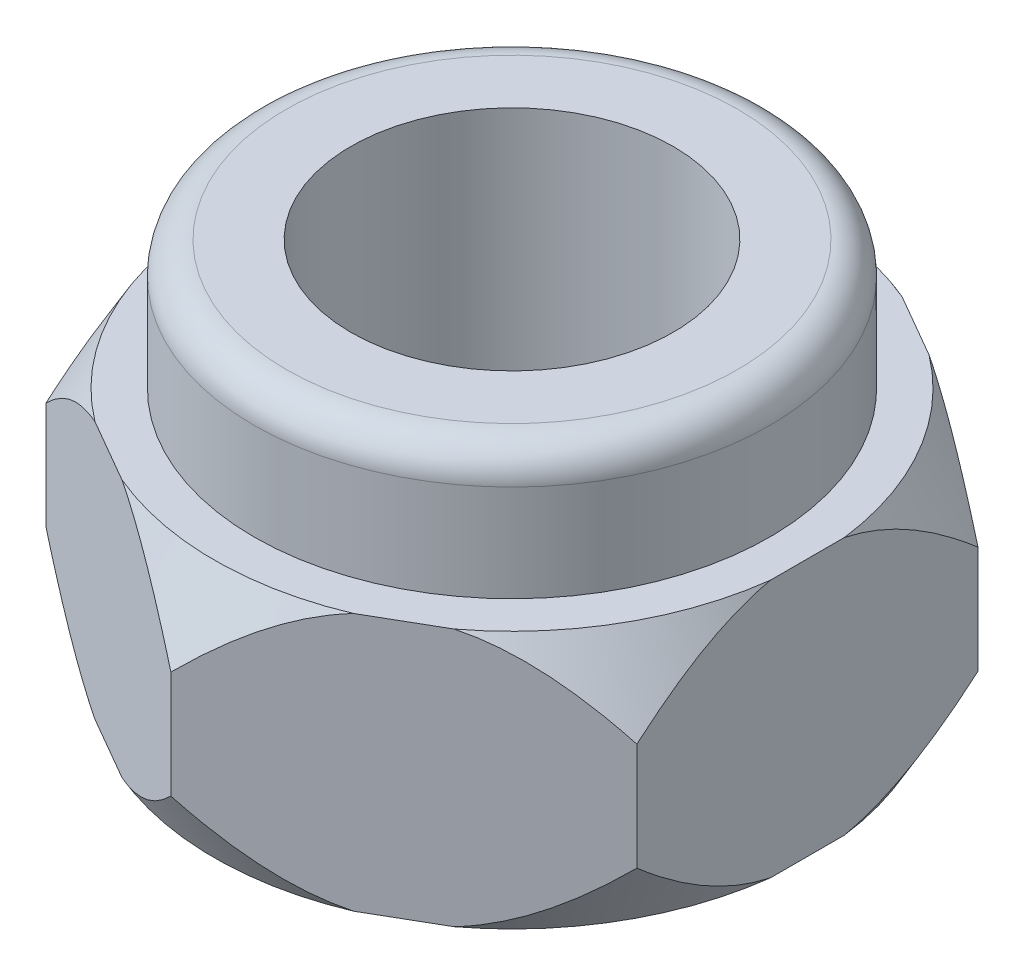
SolidWorks part; units mm, degrees
ref_plane "前视基准面" through (0, 0, 0) normal (0, 0, 1) x (1, 0, 0)
ref_plane "上视基准面" through (0, 0, 0) normal (0, 1, 0) x (1, 0, 0)
ref_plane "右视基准面" through (0, 0, 0) normal (1, 0, 0) x (0, 0, -1)
sketch "草图1" plane through (0, 0, 0) normal (0, 1, 0) x (1, 0, 0)
  line L1 (0, 3.1754) -> (-2.75, 1.5877)
  line L2 (-2.75, 1.5877) -> (-2.75, -1.5877)
  line L3 (-2.75, -1.5877) -> (0, -3.1754)
  line L4 (0, -3.1754) -> (2.75, -1.5877)
  line L5 (2.75, -1.5877) -> (2.75, 1.5877)
  line L6 (2.75, 1.5877) -> (0, 3.1754)
  circle A0 centre (0, 0) radius 2.75 construction
  circle A1 centre (0, 0) radius 1.5
  dimension "D1" = 3
  dimension "D2" = 5.5
extrude "凸台-拉伸1" add sketch "草图1" along normal blind 2.4
cosmetic thread "装饰螺纹线1" parameters "D2"=9
sketch "草图3" plane through (0, 0, 0) normal (1, 0, 0) x (0, 0, -1)
  line L0 (0, 2.4) -> (0, 7.2) construction
  line L1 (-1.5877, 2.4) -> (1.5877, 2.4) construction
  line L2 (0, 7.2) -> (3.4641, 1.2) construction
  line L3 (0.3843, 7.2) -> (4.0835, 7.2)
  line L4 (4.0835, 7.2) -> (4.0835, -4.8)
  line L5 (-1.5877, 1.2) -> (6.6733, 1.2) construction
  line L6 (-1.5877, 2.4) -> (-1.5877, 0) construction
  line L7 (0.3843, 6.5344) -> (0.3843, 7.2)
  line L8 (0.2977, -4.8) -> (4.0835, -4.8)
  line L9 (0, -4.8) -> (3.4641, 1.2) construction
  line L10 (0.2977, -4.2844) -> (0.2977, -4.8)
  line L11 (0.3843, 6.5344) -> (3.4641, 1.2)
  line L12 (3.4641, 1.2) -> (0.2977, -4.2844)
  dimension "D1" = 4.8
  dimension "D2" = 30
revolve "切除-旋转7" cut sketch "草图3" angle 360 about axis through (0, 2.4, 0) along (0, -1, 0)
sketch "草图4" plane through (0, 2.4, 0) normal (0, 1, 0) x (1, 0, 0)
  circle A0 centre (0, 0) radius 1.5
  circle A1 centre (0, 0) radius 2.4
  dimension "D1" = 4.8
extrude "凸台-拉伸3" add sketch "草图4" along normal blind 1.2
fillet "圆角5" radius 0.3 1 edges at (0, 3.6, 2.4)
